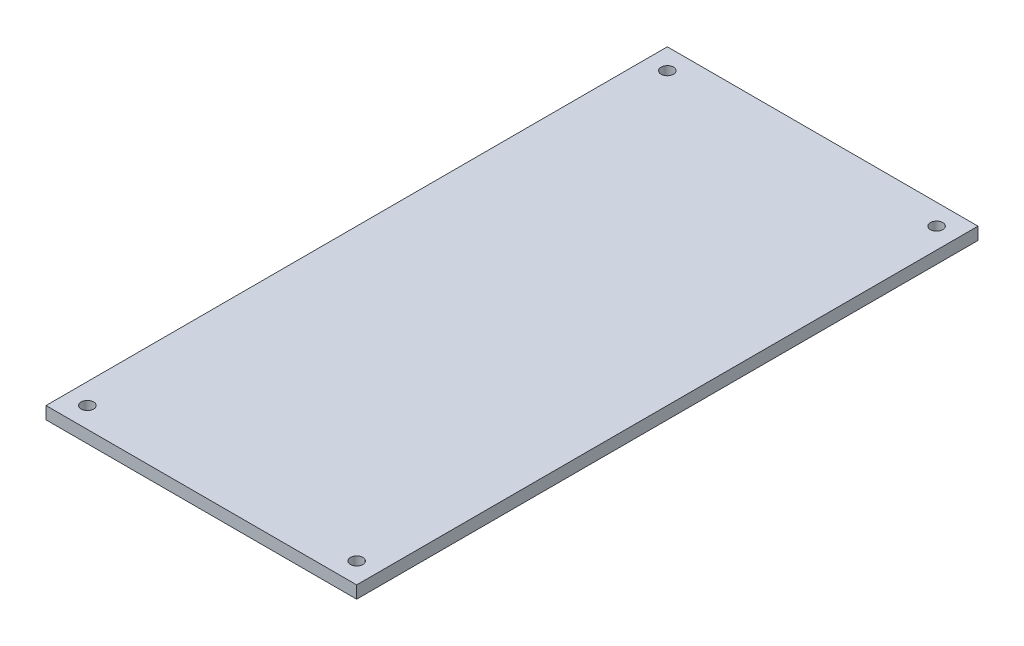
SolidWorks part; units mm, degrees
ref_plane "Front Plane" through (0, 0, 0) normal (0, 0, 1) x (1, 0, 0)
ref_plane "Top Plane" through (0, 0, 0) normal (0, 1, 0) x (1, 0, 0)
ref_plane "Right Plane" through (0, 0, 0) normal (1, 0, 0) x (0, 0, -1)
sketch "Sketch1" plane through (0, 0, 0) normal (0, 1, 0) x (1, 0, 0)
  line L1 (-50, 100) -> (25, 100)
  line L2 (-50, 100) -> (-50, -50)
  line L3 (-50, -50) -> (25, -50)
  line L4 (25, 100) -> (25, -50)
  point P0 (0, 0)
  dimension "D1" = 150
  dimension "D2" = 75
extrude "Boss-Extrude1" add sketch "Sketch1" along normal blind 3
sketch "Sketch2" plane through (0, 3, 0) normal (0, 1, 0) x (1, 0, 0)
  line L0 (-50, 100) -> (-50, -50) construction
  line L1 (25, 100) -> (-50, 100) construction
  line L2 (-50, -50) -> (25, -50) construction
  line L3 (25, -50) -> (25, 100) construction
  circle A0 centre (-45, 95) radius 1.5
  circle A1 centre (20, 95) radius 1.5
  circle A2 centre (20, -45) radius 1.5
  circle A3 centre (-45, -45) radius 1.5
  dimension "D1" = 3
  dimension "D2" = 3
  dimension "D3" = 3
  dimension "D4" = 3
  dimension "D5" = 5
  dimension "D6" = 5
  dimension "D7" = 5
  dimension "D8" = 5
  dimension "D9" = 5
  dimension "D10" = 5
  dimension "D11" = 5
  dimension "D12" = 5
extrude "Cut-Extrude1" cut sketch "Sketch2" against normal blind 20
